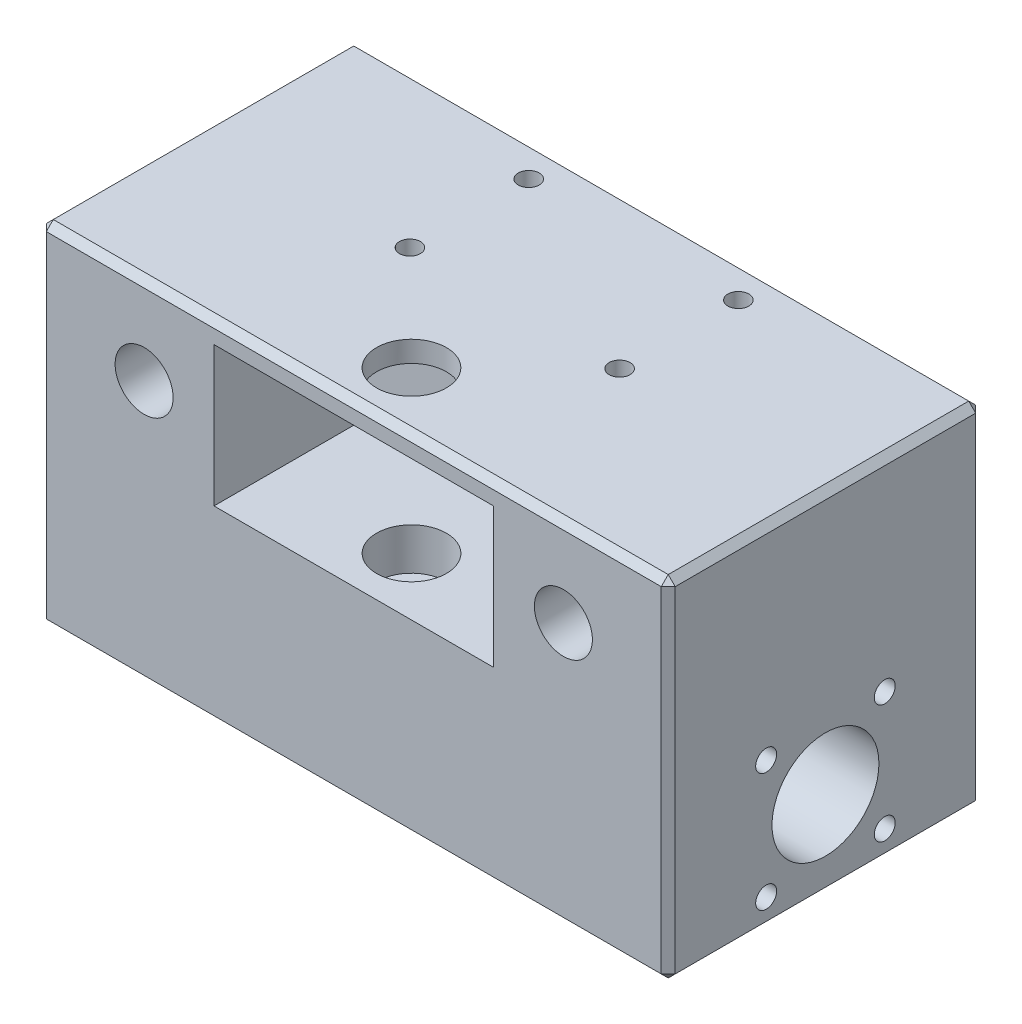
SolidWorks part; units mm, degrees
ref_plane "前视基准面" through (0, 0, 0) normal (0, 0, 1) x (1, 0, 0)
ref_plane "上视基准面" through (0, 0, 0) normal (0, 1, 0) x (1, 0, 0)
ref_plane "右视基准面" through (0, 0, 0) normal (1, 0, 0) x (0, 0, -1)
sketch "Sketch1" plane through (0, 0, 0) normal (0, 1, 0) x (1, 0, 0)
  line L1 (-45, 22.5) -> (45, 22.5)
  line L2 (-45, 22.5) -> (-45, -22.5)
  line L3 (-45, -22.5) -> (45, -22.5)
  line L4 (45, 22.5) -> (45, -22.5)
  line L5 (-45, 22.5) -> (45, -22.5) construction
  line L6 (-45, -22.5) -> (45, 22.5) construction
  point P0 (0, 0)
  dimension "D1" = 90
  dimension "D2" = 45
extrude "Boss-Extrude1" add sketch "Sketch1" along normal blind 50
sketch "Sketch2" plane through (0, 0, 22.5) normal (0, 0, 1) x (1, 0, 0)
  line L0 (-45, 25) -> (45, 25) construction
  line L1 (-45, 50) -> (-45, 0) construction
  line L2 (45, 50) -> (45, 0) construction
  line L3 (-45, 50) -> (45, 50) construction
  line L4 (0, -6.1777) -> (0, 0) construction
  circle A0 centre (-30, 37.5) radius 4.15
  circle A1 centre (30, 37.5) radius 4.15
  dimension "D1" = 8.3
  dimension "D2" = 30
  dimension "D3" = 12.5
extrude "Cut-Extrude1" cut sketch "Sketch2" against normal blind 28.2967
sketch "Sketch3" plane through (45, 0, 0) normal (1, 0, 0) x (0, 0, -1)
  line L0 (-22.5, 0) -> (22.5, 0) construction
  circle A0 centre (0, 12.5) radius 7.65
  dimension "D1" = 12.5
  dimension "D2" = 15.3
extrude "Cut-Extrude2" cut sketch "Sketch3" against normal through all
sketch "Sketch4" plane through (45, 0, 0) normal (1, 0, 0) x (0, 0, -1)
  line L0 (0, 12.5) -> (-8.4853, 20.9853) construction
  line L1 (0, 12.5) -> (-12, 12.5) construction
  circle A0 centre (0, 12.5) radius 12 construction
  circle A1 centre (-8.4853, 20.9853) radius 1.5
  circle A2 centre (8.4853, 20.9853) radius 1.5
  circle A3 centre (8.4853, 4.0147) radius 1.5
  circle A4 centre (-8.4853, 4.0147) radius 1.5
  point P15 (0, 12.5)
  dimension "D1" = 24
  dimension "D3" = 3
  dimension "D4" = 4
  dimension "D2" = 45
extrude "Cut-Extrude3" cut sketch "Sketch4" against normal blind 10
mirror "Mirror1" about plane through (0, 0, 0) normal (1, 0, 0) of "Cut-Extrude3"
chamfer "Chamfer1" distance 1 angle 45 12 edges at (-45, 0, 0) (45, 0, 0) (45, 25, -22.5) (0, 0, -22.5) (-45, 25, -22.5) (0, 50, 22.5) (-45, 50, 0) (0, 50, -22.5) (45, 50, 0) (45, 25, 22.5) (0, 0, 22.5) (-45, 25, 22.5)
sketch "Sketch5" plane through (0, 50, 0) normal (0, 1, 0) x (1, 0, 0)
  line L0 (0, 0) -> (0, 22.5383) construction
  circle A0 centre (15, 0.5383) radius 1.5
  circle A1 centre (15, 17.5383) radius 1.5
  circle A2 centre (-15, 17.5383) radius 1.5
  circle A3 centre (-15, 0.5383) radius 1.5
  point P7 (0, 0)
  dimension "D1" = 3
  dimension "D2" = 15
  dimension "D3" = 22
  dimension "D4" = 3
  dimension "D5" = 17
extrude "Cut-Extrude4" cut sketch "Sketch5" against normal blind 10
sketch "Sketch6" plane through (0, 0, 22.5) normal (0, 0, 1) x (1, 0, 0)
  line L1 (-20, 27) -> (20, 27)
  line L2 (-20, 27) -> (-20, 47)
  line L3 (-20, 47) -> (20, 47)
  line L4 (20, 27) -> (20, 47)
  line L5 (-20, 27) -> (20, 47) construction
  line L6 (-20, 47) -> (20, 27) construction
  line L8 (-44, 50) -> (44, 50) construction
  point P0 (0, 37)
  point P5 (0, 32.8806)
  point P8 (-7.9636, -14.5978)
  dimension "D1" = 3
  dimension "D2" = 20
  dimension "D3" = 40
extrude "Cut-Extrude5" cut sketch "Sketch6" against normal blind 20 contours L3 L4 L1 L2
sketch "Sketch7" plane through (0, 50, 0) normal (0, 1, 0) x (1, 0, 0)
  circle A1 centre (0, -14.2418) radius 5
  point P2 (0, 0)
  point P3 (0, 0)
  dimension "D1" = 10
  dimension "D2" = 14.2418
extrude "Cut-Extrude6" cut sketch "Sketch7" against normal offset from surface (29 mm away) 6 up to face at (0, 27, 12.5) offset beyond the face yes
